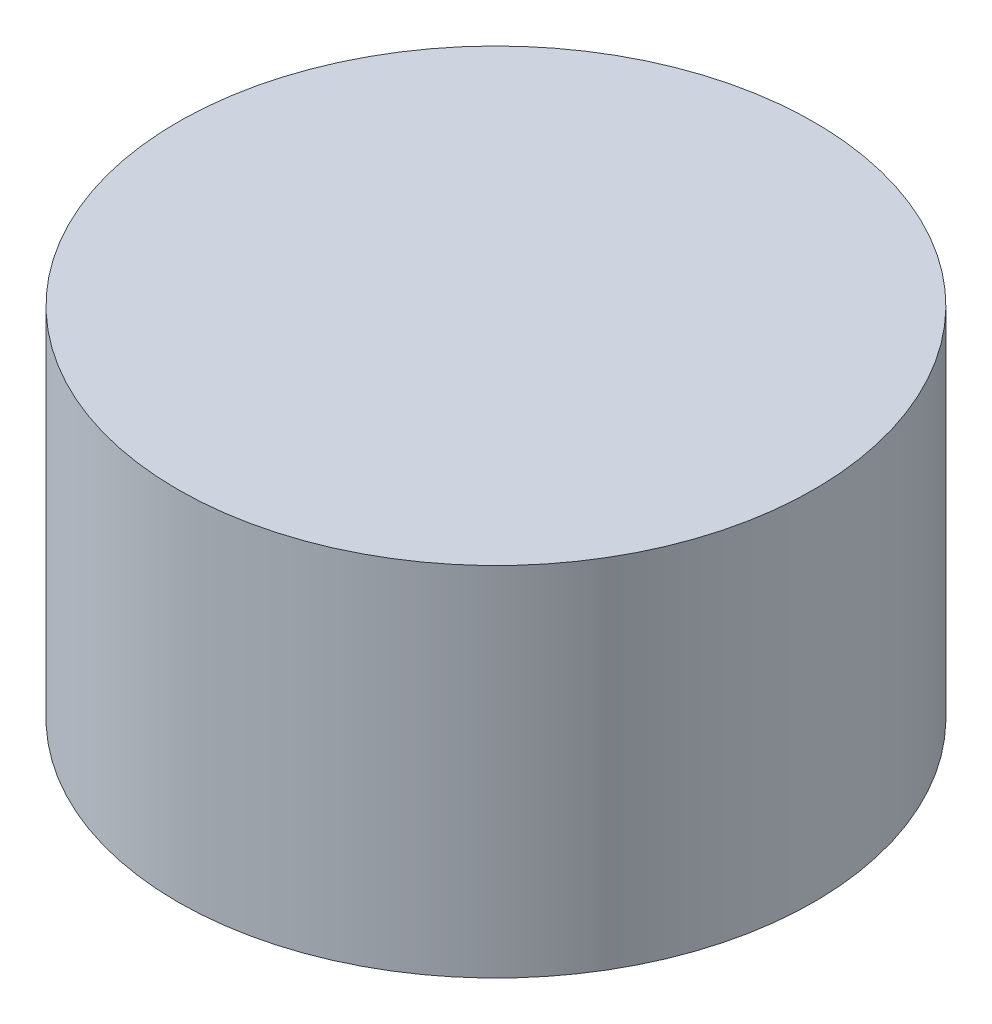
SolidWorks part; units mm, degrees
ref_plane "Front Plane" through (0, 0, 0) normal (0, 0, 1) x (1, 0, 0)
ref_plane "Top Plane" through (0, 0, 0) normal (0, 1, 0) x (1, 0, 0)
ref_plane "Right Plane" through (0, 0, 0) normal (1, 0, 0) x (0, 0, -1)
sketch "Sketch1" plane through (0, 0, 0) normal (0, 1, 0) x (1, 0, 0)
  circle A0 centre (0, 0) radius 14.25
  dimension "D1" = 28.5
extrude "Boss-Extrude1" add sketch "Sketch1" along normal blind 16
